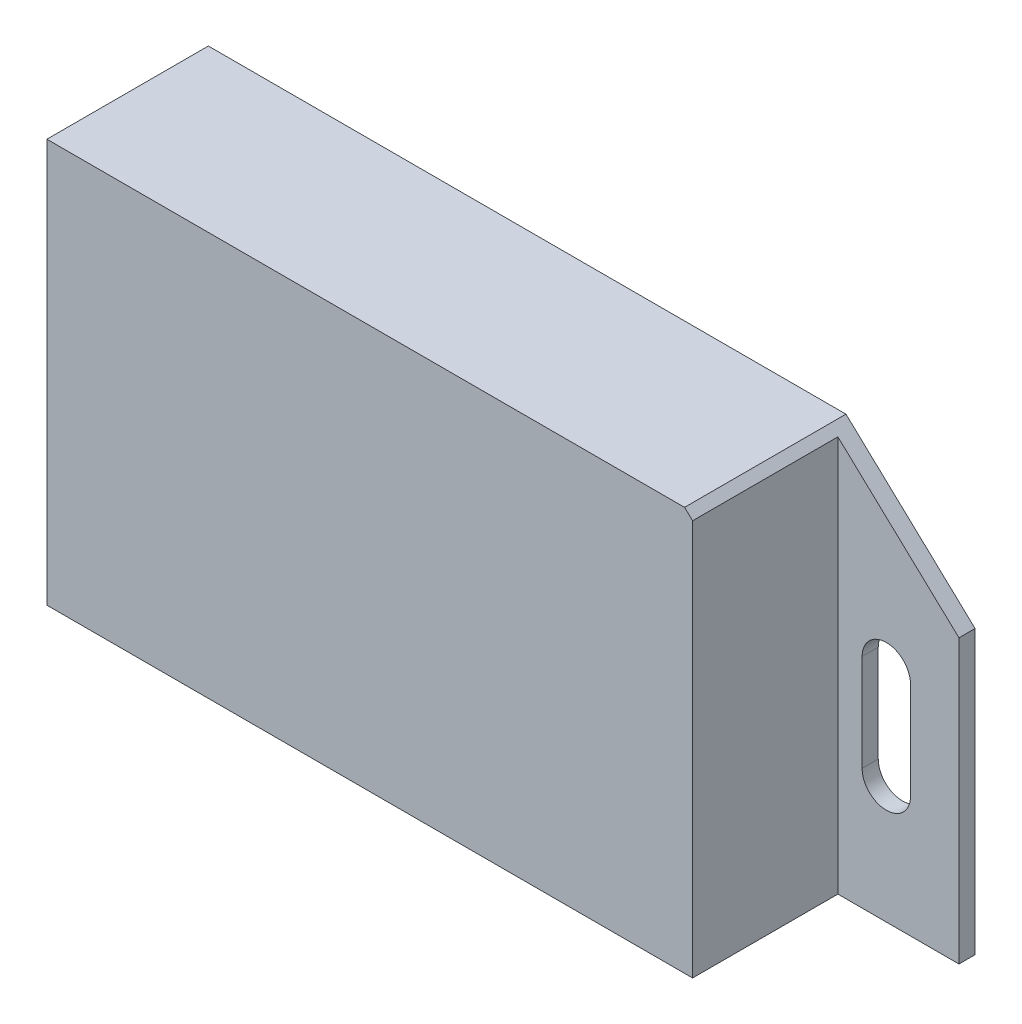
SolidWorks part; units mm, degrees
ref_plane "前视基准面" through (0, 0, 0) normal (0, 0, 1) x (1, 0, 0)
ref_plane "上视基准面" through (0, 0, 0) normal (0, 1, 0) x (1, 0, 0)
ref_plane "右视基准面" through (0, 0, 0) normal (1, 0, 0) x (0, 0, -1)
other "Configuration Table"
sketch "草图1" plane through (0, 0, 0) normal (0, 0, 1) x (1, 0, 0)
  line L0 (-27.5, -12.5) -> (27.5, -12.5)
  line L1 (27.5, -12.5) -> (27.5, 12.5)
  line L2 (27.5, 12.5) -> (-27.5, 12.5)
  line L3 (-27.5, 12.5) -> (-27.5, -12.5)
  dimension "D1" = 55
  dimension "D2" = 25
extrude "凸台-拉伸1" add sketch "草图1" against normal blind 10
sketch "草图2" plane through (0, -12.5, 0) normal (0, -1, 0) x (1, 0, 0)
  line L0 (10.2, -1.8) -> (-10.2, -1.8)
  line L1 (-10.2, -1.8) -> (-10.2, -3.2)
  line L2 (-10.2, -3.2) -> (10.2, -3.2)
  line L3 (10.2, -3.2) -> (10.2, -1.8)
  line L4 (-27.5, -10) -> (-27.5, 0) construction
  line L5 (-27.5, 0) -> (27.5, 0) construction
  dimension "D1" = 17.3
  dimension "D2" = 37.7
  dimension "D3" = 1.8
  dimension "D4" = 3.2
extrude "切除-拉伸1" cut sketch "草图2" against normal blind 2
sketch "草图3" plane through (0, -12.5, 0) normal (0, -1, 0) x (1, 0, 0)
  line L0 (-20, -9) -> (-20, 0)
  line L1 (-20, 0) -> (-27.5, 0)
  line L2 (-27.5, 0) -> (-27.5, -9)
  line L3 (-27.5, -9) -> (-20, -9)
  line L4 (-10.2, -1.8) -> (-10.2, -3.2) construction
  line L5 (-10.2, -3.2) -> (10.2, -3.2) construction
  dimension "D1" = 9.8
  dimension "D2" = 17.3
  dimension "D3" = 3.2
  dimension "D4" = 5.8
extrude "切除-拉伸2" cut sketch "草图3" against normal through all
sketch "草图4" plane through (0, -12.5, 0) normal (0, -1, 0) x (1, 0, 0)
  line L0 (20, 0) -> (20, -9)
  line L1 (20, -9) -> (27.5, -9)
  line L2 (27.5, -9) -> (27.5, 0)
  line L3 (27.5, 0) -> (20, 0)
  line L4 (-27.5, -10) -> (-27.5, -9) construction
  line L5 (-27.5, -10) -> (27.5, -10) construction
  dimension "D1" = 47.5
  dimension "D2" = 55
  dimension "D3" = 1
  dimension "D4" = 10
extrude "切除-拉伸3" cut sketch "草图4" against normal through all
sketch "草图5" plane through (0, 0, -10) normal (0, 0, -1) x (-1, 0, 0)
  line L0 (21.5, 1) -> (21.5, -5)
  line L1 (24.5, -5) -> (24.5, 1)
  line L2 (27.5, 12.5) -> (27.5, -12.5) construction
  line L3 (-27.5, 12.5) -> (27.5, 12.5) construction
  arc A0 (21.5, -5) -> (24.5, -5) centre (23, -5) ccw
  arc A1 (24.5, 1) -> (21.5, 1) centre (23, 1) ccw
  dimension "D1" = 1.5
  dimension "D2" = 4.5
  dimension "D3" = 11.5
  dimension "D4" = 17.5
extrude "切除-拉伸4" cut sketch "草图5" against normal through all
sketch "草图6" plane through (0, 0, -10) normal (0, 0, -1) x (-1, 0, 0)
  line L0 (-24.5, 1) -> (-24.5, -5)
  line L1 (-21.5, -5) -> (-21.5, 1)
  line L2 (24.5, -5) -> (24.5, 1) construction
  arc A0 (-21.5, 1) -> (-24.5, 1) centre (-23, 1) ccw
  arc A1 (-24.5, -5) -> (-21.5, -5) centre (-23, -5) ccw
  dimension "D1" = 1.5
  dimension "D2" = 47.5
  dimension "D3" = 6
extrude "切除-拉伸5" cut sketch "草图6" against normal through all
ref_plane "基准面1" through (0, 0, -2.8) normal (0, 0, -1) x (-1, 0, 0)
sketch "草图7" plane through (0, 0, -2.8) normal (0, 0, -1) x (-1, 0, 0)
  line L0 (-10, -12.5) -> (-10, -13.5)
  line L1 (-10, -13.5) -> (10.9959, -13.5)
  line L2 (10.9959, -13.5) -> (10.9959, -12.5)
  line L3 (10.9959, -12.5) -> (-10, -12.5)
  dimension "D1" = 20.9959
  dimension "D2" = 1
extrude "凸台-拉伸2" add sketch "草图7" against normal blind 0.8
sketch "草图8" plane through (0, -12.5, 0) normal (0, -1, 0) x (1, 0, 0)
  line L0 (-10, -7.5) -> (-10, -9)
  line L1 (-10, -9) -> (10, -9)
  line L2 (10, -9) -> (10, -7.5)
  line L3 (10, -7.5) -> (-10, -7.5)
  line L4 (-10.9959, -2) -> (-10.9959, -2.8) construction
  line L5 (-10.9959, -2) -> (-10.2, -2) construction
  dimension "D1" = 0.9959
  dimension "D2" = 20.9959
  dimension "D3" = 5.5
  dimension "D4" = 7
extrude "切除-拉伸6" cut sketch "草图8" against normal blind 10
chamfer "倒角1" distance 8 angle 43.152 2 edges at (27.5, 12.5, -9.5) (-27.5, 12.5, -9.5)
